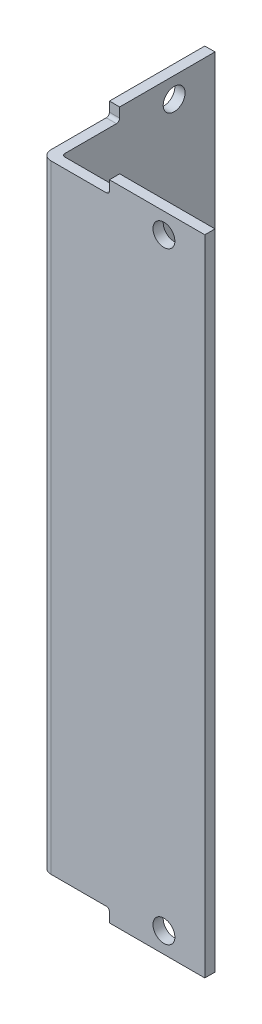
SolidWorks part; units mm, degrees
material "6061-T6 (SS)"
ref_plane "Front Plane" through (0, 0, 0) normal (0, 0, 1) x (1, 0, 0)
ref_plane "Top Plane" through (0, 0, 0) normal (0, 1, 0) x (1, 0, 0)
ref_plane "Right Plane" through (0, 0, 0) normal (1, 0, 0) x (0, 0, -1)
sketch "Sketch1" plane through (0, 0, 0) normal (0, 1, 0) x (1, 0, 0)
  line L1 (-12.7, -12.7) -> (12.7, -12.7)
  line L2 (-12.7, -12.7) -> (-12.7, 12.7)
  line L3 (-12.7, 12.7) -> (12.7, 12.7)
  line L4 (12.7, -12.7) -> (12.7, 12.7)
  line L5 (-12.7, -12.7) -> (12.7, 12.7) construction
  line L6 (-12.7, 12.7) -> (12.7, -12.7) construction
  point P0 (0, 0)
  dimension "D1" = 25.4
  dimension "D2" = 25.4
extrude "Boss-Extrude1" add sketch "Sketch1" along normal mid plane 113.5
sketch "Sketch2" plane through (0, 56.75, 0) normal (0, 1, 0) x (1, 0, 0)
  line L0 (-12.7, 12.7) -> (-12.7, -12.7) construction
  line L1 (12.7, 12.7) -> (-11.1125, 12.7)
  line L2 (12.7, 12.7) -> (12.7, -11.1125)
  line L3 (12.7, -11.1125) -> (-11.1125, -11.1125)
  line L4 (-11.1125, 12.7) -> (-11.1125, -11.1125)
  line L5 (-12.7, -12.7) -> (12.7, -12.7) construction
  dimension "D1" = 1.5875
  dimension "D2" = 1.5875
extrude "Cut-Extrude1" cut sketch "Sketch2" against normal through all
fillet "Fillet1" radius 0.508 1 edges at (-11.1125, 0, 11.1125)
hole_wizard "M3 Clearance Hole1" positions "Sketch3" profile "Sketch4" hole size "M3" standard "ANSI Metric" end condition through all
sketch "Sketch3" plane through (0, 0, 12.7) normal (0, 0, 1) x (1, 0, 0)
  line L1 (-12.7, 56.75) -> (12.7, 56.75) construction
  line L2 (12.7, 56.75) -> (12.7, -56.75) construction
  point P0 (6.35, 47.075)
  dimension "D1" = 6.35
  dimension "D2" = 9.675
sketch "Sketch4" plane through (6.35, 47.075, 12.7) normal (1, 0, 0) x (0, -1, 0)
  line L0 (0, 0) -> (0, 25.4)
  line L1 (0, 25.4) -> (1.7, 25.4)
  line L2 (1.7, 25.4) -> (1.7, 0)
  line L5 (1.7, 0) -> (0, 0)
  line L11 (0, -6.35) -> (0, 107.95) construction
  dimension "Thru Hole Dia." = 3.4
  dimension "Thru Hole Depth" = 25.4
hole_wizard "M3 Clearance Hole2" positions "Sketch5" profile "Sketch6" hole size "M3" standard "ANSI Metric" end condition through all
sketch "Sketch5" plane through (-12.7, 0, 0) normal (-1, 0, 0) x (0, 0, 1)
  line L1 (-12.7, 56.75) -> (12.7, 56.75) construction
  line L2 (-12.7, 56.75) -> (-12.7, -56.75) construction
  point P0 (-6.35, 47.075)
  dimension "D1" = 6.35
  dimension "D2" = 9.675
sketch "Sketch6" plane through (-12.7, 47.075, -6.35) normal (0, 1, 0) x (0, 0, 1)
  line L0 (0, 0) -> (0, 25.4)
  line L1 (0, 25.4) -> (1.7, 25.4)
  line L2 (1.7, 25.4) -> (1.7, 0)
  line L5 (1.7, 0) -> (0, 0)
  line L11 (0, -6.35) -> (0, 107.95) construction
  dimension "Thru Hole Dia." = 3.4
  dimension "Thru Hole Depth" = 25.4
hole_wizard "M3 Clearance Hole3" positions "Sketch7" profile "Sketch8" hole size "M3" standard "ANSI Metric" end condition through all
sketch "Sketch7" plane through (0, 0, 12.7) normal (0, 0, 1) x (1, 0, 0)
  line L2 (-12.7, -56.75) -> (12.7, -56.75) construction
  line L3 (12.7, 56.75) -> (12.7, -56.75) construction
  point P0 (6.35, -46.575)
  dimension "D1" = 6.35
  dimension "D2" = 10.175
sketch "Sketch8" plane through (6.35, -46.575, 12.7) normal (1, 0, 0) x (0, -1, 0)
  line L0 (0, 0) -> (0, 25.4)
  line L1 (0, 25.4) -> (1.7, 25.4)
  line L2 (1.7, 25.4) -> (1.7, 0)
  line L5 (1.7, 0) -> (0, 0)
  line L11 (0, -6.35) -> (0, 107.95) construction
  dimension "Thru Hole Dia." = 3.4
  dimension "Thru Hole Depth" = 25.4
hole_wizard "M3 Clearance Hole4" positions "Sketch9" profile "Sketch10" hole size "M3" standard "ANSI Metric" end condition through all
sketch "Sketch9" plane through (-12.7, 0, 0) normal (-1, 0, 0) x (0, 0, 1)
  line L1 (-12.7, -56.75) -> (12.7, -56.75) construction
  line L2 (-12.7, 56.75) -> (-12.7, -56.75) construction
  point P0 (-6.35, -46.575)
  dimension "D1" = 6.35
  dimension "D2" = 10.175
sketch "Sketch10" plane through (-12.7, -46.575, -6.35) normal (0, 1, 0) x (0, 0, 1)
  line L0 (0, 0) -> (0, 25.4)
  line L1 (0, 25.4) -> (1.7, 25.4)
  line L2 (1.7, 25.4) -> (1.7, 0)
  line L5 (1.7, 0) -> (0, 0)
  line L11 (0, -6.35) -> (0, 107.95) construction
  dimension "Thru Hole Dia." = 3.4
  dimension "Thru Hole Depth" = 25.4
fillet "Fillet2" radius 1.5 1 edges at (-12.7, 0, 12.7)
sketch "Sketch11" plane through (-12.7, 0, 0) normal (-1, 0, 0) x (0, 0, 1)
  line L0 (12.7, 56.75) -> (12.7, -56.75) construction
  line L1 (-12.7, 56.75) -> (4.2, 56.75)
  line L2 (-12.7, 56.75) -> (-12.7, 50.25)
  line L3 (-12.7, 50.25) -> (4.2, 50.25)
  line L4 (4.2, 56.75) -> (4.2, 50.25)
  line L6 (-12.7, -56.75) -> (4.2, -56.75)
  line L7 (-12.7, -56.75) -> (-12.7, -49.75)
  line L8 (-12.7, -49.75) -> (4.2, -49.75)
  line L9 (4.2, -56.75) -> (4.2, -49.75)
  dimension "D1" = 8.5
  dimension "D2" = 6.5
  dimension "D3" = 7
extrude "Cut-Extrude2" cut sketch "Sketch11" against normal up to next
sketch "Sketch12" plane through (0, 0, 12.7) normal (0, 0, 1) x (1, 0, 0)
  line L0 (-12.7, -56.75) -> (-12.7, 56.75) construction
  line L1 (12.7, 56.75) -> (-4.2, 56.75)
  line L2 (12.7, 56.75) -> (12.7, 50.25)
  line L3 (12.7, 50.25) -> (-4.2, 50.25)
  line L4 (-4.2, 56.75) -> (-4.2, 50.25)
  line L5 (12.7, -56.75) -> (-4.2, -56.75)
  line L6 (12.7, -56.75) -> (12.7, -49.75)
  line L7 (12.7, -49.75) -> (-4.2, -49.75)
  line L8 (-4.2, -56.75) -> (-4.2, -49.75)
  dimension "D1" = 8.5
  dimension "D2" = 7
  dimension "D3" = 8.5
  dimension "D4" = 6.5
extrude "Cut-Extrude3" cut sketch "Sketch12" against normal up to next
fillet "Fillet3" radius 3.81 4 edges at (-4.2, -49.75, 11.9062) (-11.9063, -49.75, 4.2) (-11.9063, 50.25, 4.2) (-4.2, 50.25, 11.9062)
sketch "Sketch13" plane through (-12.7, 0, 0) normal (-1, 0, 0) x (0, 0, 1)
  line L0 (4.2, -56.75) -> (4.2, 56.75) construction
  line L9 (2.7, -56.75) -> (2.7, 56.75) construction
  line L10 (-12.7, 50.25) -> (-12.7, -49.75) construction
  line L11 (2.7, -43.4) -> (-12.7, -43.4)
  line L12 (2.7, -43.4) -> (2.7, 43.9)
  line L13 (2.7, 43.9) -> (-12.7, 43.9)
  line L14 (-12.7, -43.4) -> (-12.7, 43.9)
  circle A2 centre (-6.35, 47.075) radius 1.7 construction
  circle A3 centre (-6.35, -46.575) radius 1.7 construction
  dimension "D2" = 3.175
  dimension "D3" = 3.175
  dimension "D1" = 1.5
extrude "Cut-Extrude4" cut sketch "Sketch13" against normal up to next
sketch "Sketch14" plane through (0, 0, 12.7) normal (0, 0, 1) x (1, 0, 0)
  line L0 (-4.2, 56.75) -> (-4.2, -56.75) construction
  line L1 (-2.7, 56.75) -> (-2.7, -56.75) construction
  line L2 (12.7, 50.25) -> (12.7, -49.75) construction
  line L3 (-2.7, -43.4) -> (12.7, -43.4)
  line L4 (-2.7, -43.4) -> (-2.7, 43.9)
  line L5 (-2.7, 43.9) -> (12.7, 43.9)
  line L6 (12.7, -43.4) -> (12.7, 43.9)
  circle A0 centre (6.35, 47.075) radius 1.7 construction
  circle A1 centre (6.35, -46.575) radius 1.7 construction
  dimension "D2" = 3.175
  dimension "D3" = 3.175
  dimension "D1" = 1.5
extrude "Cut-Extrude5" cut sketch "Sketch14" against normal up to next
chamfer "Chamfer2" distance 6.35 angle 45 4 edges at (-11.9063, 43.9, 2.7) (-2.7, 43.9, 11.9062) (-2.7, -43.4, 11.9062) (-11.9062, -43.4, 2.7)
fillet "Fillet5" radius 3.81 8 edges at (3.65, -43.4, 11.9062) (-2.7, -37.05, 11.9062) (-11.9063, -43.4, -3.65) (-11.9063, -37.05, 2.7) (-11.9063, 43.9, -3.65) (-11.9063, 37.55, 2.7) (-2.7, 37.55, 11.9062) (3.65, 43.9, 11.9062)
sketch "Sketch15" plane through (0, 56.75, 0) normal (0, 1, 0) x (1, 0, 0)
  line L0 (-11.2, -12.7) -> (-4.2, -12.7) construction
  line L1 (-12.7, -12.7) -> (-0.39, -12.7)
  line L2 (-12.7, -12.7) -> (-12.7, -0.39)
  line L3 (-12.7, -0.39) -> (-0.39, -0.39)
  line L4 (-0.39, -12.7) -> (-0.39, -0.39)
  line L5 (-12.7, -4.2) -> (-12.7, -11.2) construction
  line L6 (-0.39, -11.1125) -> (-0.39, -12.7) construction
extrude "Cut-Extrude6" cut sketch "Sketch15" against normal up to surface (6.5 mm away) up to face at (6.155, 50.25, 11.9062)
sketch "Sketch16" plane through (0, 50.25, 0) normal (0, 1, 0) x (1, 0, 0)
  line L0 (-11.2, -12.7) -> (12.7, -12.7) construction
  line L1 (-12.7, -12.7) -> (-5.7, -12.7)
  line L2 (-12.7, -12.7) -> (-12.7, -5.7)
  line L3 (-12.7, -5.7) -> (-5.7, -5.7)
  line L4 (-5.7, -12.7) -> (-5.7, -5.7)
  line L5 (-12.7, 12.7) -> (-12.7, -11.2) construction
  dimension "D1" = 7
  dimension "D2" = 7
sketch "Sketch17" plane through (0, -56.75, 0) normal (0, -1, 0) x (1, 0, 0)
  line L0 (-11.2, 12.7) -> (-4.2, 12.7) construction
  line L1 (-12.7, 12.7) -> (-0.39, 12.7)
  line L2 (-12.7, 12.7) -> (-12.7, 0.39)
  line L3 (-12.7, 0.39) -> (-0.39, 0.39)
  line L4 (-0.39, 12.7) -> (-0.39, 0.39)
  line L5 (-12.7, 4.2) -> (-12.7, 11.2) construction
  line L6 (-11.1125, 0.39) -> (-12.7, 0.39) construction
  line L7 (-0.39, 12.7) -> (-0.39, 11.1125) construction
extrude "Cut-Extrude8" cut sketch "Sketch17" against normal up to surface (7 mm away) up to face at (6.155, -49.75, 11.9062)
sketch "Sketch18" plane through (-12.7, 0, 0) normal (-1, 0, 0) x (0, 0, 1)
  line L0 (-12.7, -43.4) -> (-5.2282, -43.4) construction
  line L1 (5.7, -43.4) -> (11.2, -43.4)
  line L2 (5.7, -43.4) -> (5.7, -40.4)
  line L3 (5.7, -40.4) -> (11.2, -40.4)
  line L4 (11.2, -43.4) -> (11.2, -40.4)
  line L5 (12.7, 50.25) -> (12.7, -49.75) construction
  point P8 (8.45, -40.4)
  dimension "D1" = 5.5
  dimension "D2" = 3
  dimension "D3" = 4.25
sketch "Sketch19" plane through (0, -49.75, 0) normal (0, -1, 0) x (1, 0, 0)
  line L0 (12.7, 12.7) -> (-11.2, 12.7) construction
  line L1 (-12.7, 5.7) -> (-5.7, 5.7)
  line L2 (-12.7, 5.7) -> (-12.7, 12.7)
  line L3 (-12.7, 12.7) -> (-5.7, 12.7)
  line L4 (-5.7, 5.7) -> (-5.7, 12.7)
  line L5 (-12.7, 11.2) -> (-12.7, -12.7) construction
sketch "Sketch20" plane through (-12.7, 0, 0) normal (-1, 0, 0) x (0, 0, 1)
  line L0 (-12.7, 43.9) -> (-12.7, -43.4)
  line L13 (7.2, -40.4) -> (11.2, -40.4)
  line L14 (11.2, -40.4) -> (11.2, 50.25)
  line L15 (11.2, 50.25) -> (-12.7, 50.25)
  line L16 (-12.7, 50.25) -> (-12.7, 43.9)
  line L17 (-12.7, 43.9) -> (-5.2282, 43.9)
  line L18 (-2.5341, 42.7841) -> (1.5841, 38.6659)
  line L19 (2.7, 35.9718) -> (2.7, -35.4718)
  line L20 (1.5841, -38.1659) -> (-2.5341, -42.2841)
  line L21 (-5.2282, -43.4) -> (-12.7, -43.4)
  line L22 (-12.7, -43.4) -> (-12.7, -49.75)
  line L23 (-12.7, -49.75) -> (11.2, -49.75)
  line L24 (11.2, -49.75) -> (11.2, -43.4)
  line L25 (11.2, -43.4) -> (7.2, -43.4)
  line L26 (7.2, -40.4) -> (11.2, -40.4)
  line L27 (11.2, -40.4) -> (11.2, 50.25)
  line L28 (11.2, 50.25) -> (-12.7, 50.25)
  line L29 (-12.7, 50.25) -> (-12.7, 43.9)
  line L30 (-12.7, 43.9) -> (-5.2282, 43.9)
  line L31 (-2.5341, 42.7841) -> (1.5841, 38.6659)
  line L32 (2.7, 35.9718) -> (2.7, -35.4718)
  line L33 (1.5841, -38.1659) -> (-2.5341, -42.2841)
  line L34 (-5.2282, -43.4) -> (-12.7, -43.4)
  line L35 (-12.7, -43.4) -> (-12.7, -49.75)
  line L36 (-12.7, -49.75) -> (11.2, -49.75)
  line L37 (11.2, -49.75) -> (11.2, -43.4)
  line L38 (11.2, -43.4) -> (7.2, -43.4)
  arc A5 (7.2, -40.4) -> (7.2, -43.4) centre (7.2, -41.9) ccw
  arc A6 (-2.5341, 42.7841) -> (-5.2282, 43.9) centre (-5.2282, 40.09) ccw
  arc A7 (2.7, 35.9718) -> (1.5841, 38.6659) centre (-1.11, 35.9718) ccw
  arc A8 (1.5841, -38.1659) -> (2.7, -35.4718) centre (-1.11, -35.4718) ccw
  arc A9 (-5.2282, -43.4) -> (-2.5341, -42.2841) centre (-5.2282, -39.59) ccw
  arc A10 (7.2, -40.4) -> (7.2, -43.4) centre (7.2, -41.9) ccw
  arc A11 (-2.5341, 42.7841) -> (-5.2282, 43.9) centre (-5.2282, 40.09) ccw
  arc A12 (2.7, 35.9718) -> (1.5841, 38.6659) centre (-1.11, 35.9718) ccw
  arc A13 (1.5841, -38.1659) -> (2.7, -35.4718) centre (-1.11, -35.4718) ccw
  arc A14 (-5.2282, -43.4) -> (-2.5341, -42.2841) centre (-5.2282, -39.59) ccw
  line M26 (-12.7, 43.9) -> (-5.2282, 43.9)
  arc M27 (-5.2282, 43.9) -> (-2.5341, 42.7841) centre (-5.2282, 40.09) cw
  line M28 (-2.5341, 42.7841) -> (1.5841, 38.6659)
  arc M29 (1.5841, 38.6659) -> (2.7, 35.9718) centre (-1.11, 35.9718) cw
  line M30 (2.7, 35.9718) -> (2.7, -35.4718)
  arc M31 (2.7, -35.4718) -> (1.5841, -38.1659) centre (-1.11, -35.4718) cw
  line M32 (1.5841, -38.1659) -> (-2.5341, -42.2841)
  arc M33 (-2.5341, -42.2841) -> (-5.2282, -43.4) centre (-5.2282, -39.59) cw
  line M34 (-5.2282, -43.4) -> (-12.7, -43.4)
  dimension "D1" = 0
extrude "Boss-Extrude2" add sketch "Sketch20" against normal up to surface (1.5875 mm away) contours L0 M26 M34 M33 M32 M31 M30 M29 M28 M27 up to face at (-11.1125, -46.575, -4.65)
sketch "Sketch21" plane through (0, 0, 12.7) normal (0, 0, 1) x (1, 0, 0)
  line L0 (12.7, 43.9) -> (12.7, -43.4)
  line L14 (-11.2, 50.25) -> (-11.2, -49.75)
  line L15 (-11.2, -49.75) -> (12.7, -49.75)
  line L16 (12.7, -49.75) -> (12.7, -43.4)
  line L17 (12.7, -43.4) -> (5.2282, -43.4)
  line L18 (2.5341, -42.2841) -> (-1.5841, -38.1659)
  line L19 (-2.7, -35.4718) -> (-2.7, 35.9718)
  line L20 (-1.5841, 38.6659) -> (2.5341, 42.7841)
  line L21 (5.2282, 43.9) -> (12.7, 43.9)
  line L22 (12.7, 43.9) -> (12.7, 50.25)
  line L23 (12.7, 50.25) -> (-11.2, 50.25)
  line L27 (-11.2, 50.25) -> (-11.2, -49.75)
  line L28 (-11.2, -49.75) -> (12.7, -49.75)
  line L29 (12.7, -49.75) -> (12.7, -43.4)
  line L30 (12.7, -43.4) -> (5.2282, -43.4)
  line L31 (2.5341, -42.2841) -> (-1.5841, -38.1659)
  line L32 (-2.7, -35.4718) -> (-2.7, 35.9718)
  line L33 (-1.5841, 38.6659) -> (2.5341, 42.7841)
  line L34 (5.2282, 43.9) -> (12.7, 43.9)
  line L35 (12.7, 43.9) -> (12.7, 50.25)
  line L36 (12.7, 50.25) -> (-11.2, 50.25)
  arc A6 (2.5341, -42.2841) -> (5.2282, -43.4) centre (5.2282, -39.59) ccw
  arc A7 (-2.7, -35.4718) -> (-1.5841, -38.1659) centre (1.11, -35.4718) ccw
  arc A8 (-1.5841, 38.6659) -> (-2.7, 35.9718) centre (1.11, 35.9718) ccw
  arc A9 (5.2282, 43.9) -> (2.5341, 42.7841) centre (5.2282, 40.09) ccw
  arc A11 (2.5341, -42.2841) -> (5.2282, -43.4) centre (5.2282, -39.59) ccw
  arc A12 (-2.7, -35.4718) -> (-1.5841, -38.1659) centre (1.11, -35.4718) ccw
  arc A13 (-1.5841, 38.6659) -> (-2.7, 35.9718) centre (1.11, 35.9718) ccw
  arc A14 (5.2282, 43.9) -> (2.5341, 42.7841) centre (5.2282, 40.09) ccw
  line M24 (12.7, -43.4) -> (5.2282, -43.4)
  arc M25 (5.2282, -43.4) -> (2.5341, -42.2841) centre (5.2282, -39.59) cw
  line M26 (2.5341, -42.2841) -> (-1.5841, -38.1659)
  arc M27 (-1.5841, -38.1659) -> (-2.7, -35.4718) centre (1.11, -35.4718) cw
  line M28 (-2.7, -35.4718) -> (-2.7, 35.9718)
  arc M29 (-2.7, 35.9718) -> (-1.5841, 38.6659) centre (1.11, 35.9718) cw
  line M30 (-1.5841, 38.6659) -> (2.5341, 42.7841)
  arc M31 (2.5341, 42.7841) -> (5.2282, 43.9) centre (5.2282, 40.09) cw
  line M32 (5.2282, 43.9) -> (12.7, 43.9)
  dimension "D1" = 0
sketch "Sketch22" plane through (0, 50.25, 0) normal (0, 1, 0) x (1, 0, 0)
  line L0 (-12.7, 12.7) -> (-12.7, -11.2) construction
  line L1 (-12.7, -12.7) -> (-2.1125, -12.7)
  line L2 (-12.7, -12.7) -> (-12.7, -2.1125)
  line L3 (-12.7, -2.1125) -> (-2.1125, -2.1125)
  line L4 (-2.1125, -12.7) -> (-2.1125, -2.1125)
  line L5 (12.7, -12.7) -> (-11.2, -12.7) construction
  line L6 (12.7, -11.1125) -> (-10.6045, -11.1125) construction
  dimension "D1" = 9
extrude "Boss-Extrude3" add sketch "Sketch21" against normal up to surface (1.5875 mm away) contours L0 M32 M31 M30 M29 M28 M27 M26 M25 M24 up to face at (8.05, -46.575, 11.1125)
extrude "Cut-Extrude9" cut sketch "Sketch22" against normal blind 2
fillet "Fillet6" radius 0.5 2 edges at (-2.1125, 48.25, 11.9062) (-11.9063, 48.25, 2.1125)
ref_plane "Plane1" through (0, 0.25, 0) normal (0, 1, 0) x (1, 0, 0)
mirror "Mirror1" about plane through (0, 0.25, 0) normal (0, 1, 0) of "Cut-Extrude9", "Fillet6"
